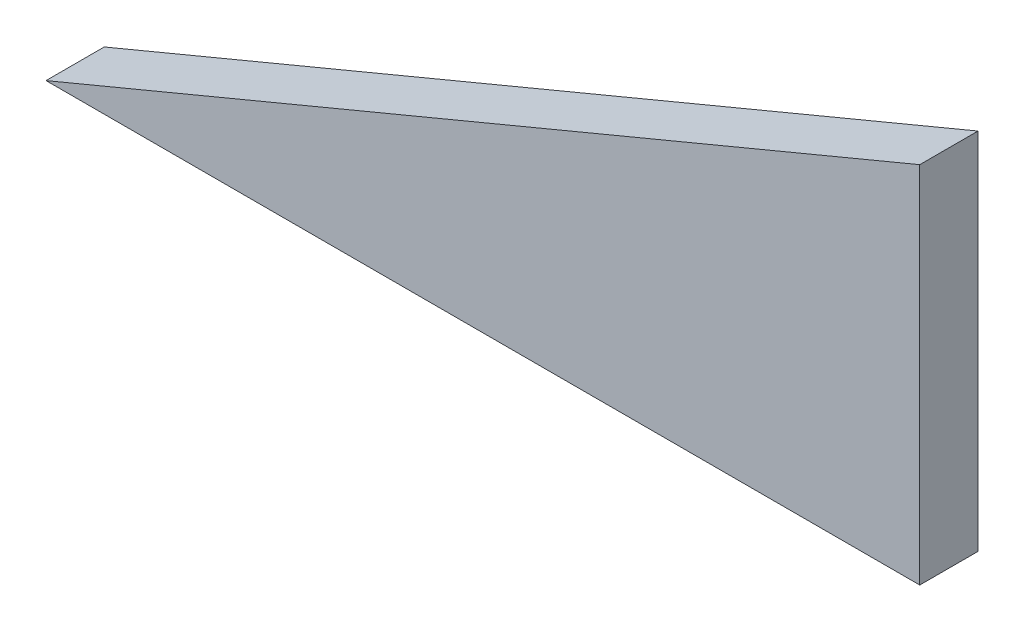
SolidWorks part; units mm, degrees
material "1.0037 (S235JR)"
ref_plane "E_Rechts" through (0, 0, 0) normal (0, 0, 1) x (1, 0, 0)
ref_plane "E_Oben" through (0, 0, 0) normal (0, 1, 0) x (1, 0, 0)
ref_plane "E_Vorne" through (0, 0, 0) normal (1, 0, 0) x (0, 0, -1)
sketch "Skizze1" plane through (0, 0, 0) normal (0, 0, 1) x (1, 0, 0)
  line L1 (0, 0) -> (0, 50)
  line L2 (0, -55) -> (0, 55) construction
  line L3 (0, 50) -> (-120, 0)
  line L4 (55, 0) -> (-55, 0) construction
  line L5 (-120, 0) -> (0, 0)
  dimension "D1" = 50
  dimension "D2" = 120
extrude "Aufsatz-Linear austragen1" add sketch "Skizze1" along normal mid plane 8
